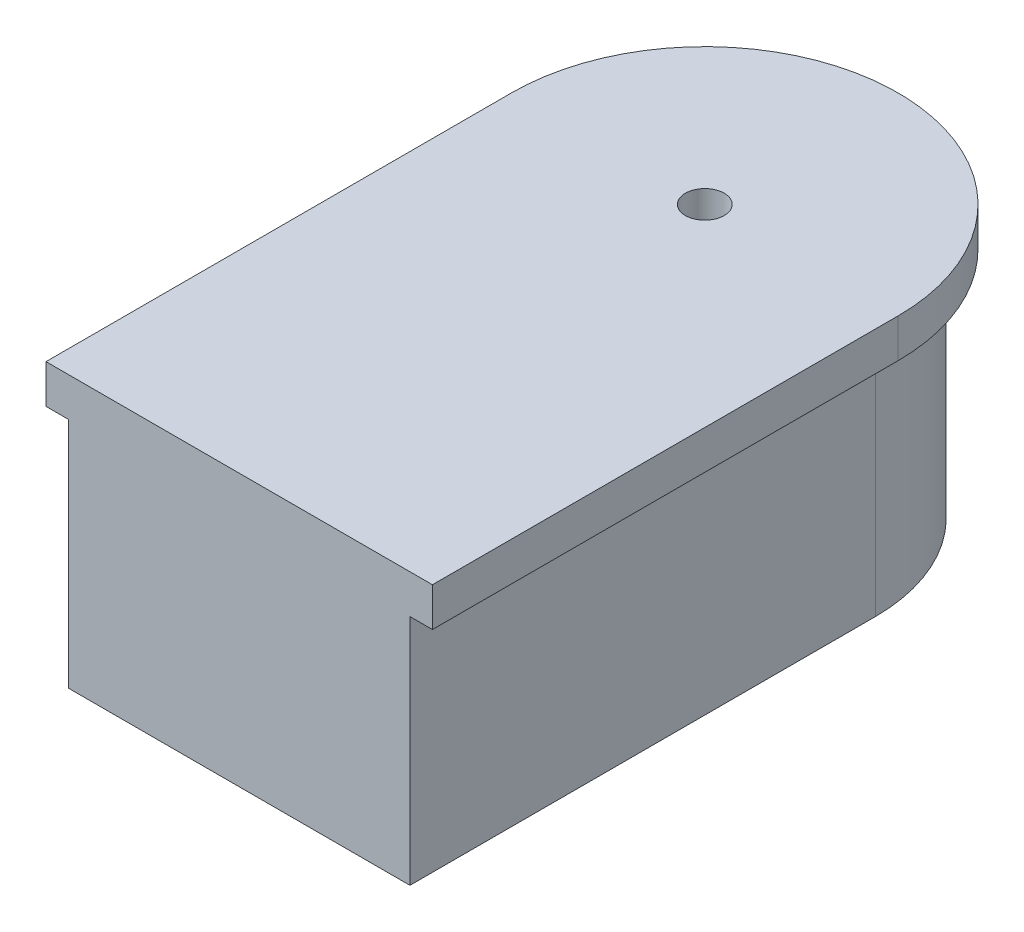
SolidWorks part; units mm, degrees
ref_plane "Front Plane" through (0, 0, 0) normal (0, 0, 1) x (1, 0, 0)
ref_plane "Top Plane" through (0, 0, 0) normal (0, 1, 0) x (1, 0, 0)
ref_plane "Right Plane" through (0, 0, 0) normal (1, 0, 0) x (0, 0, -1)
sketch "Sketch1" plane through (0, 0, 0) normal (0, 1, 0) x (1, 0, 0)
  line L1 (0, 0) -> (44, 0)
  line L2 (0, 0) -> (0, 60)
  line L4 (44, 0) -> (44, 60)
  arc A0 (0, 60) -> (44, 60) centre (22, 60) cw
  dimension "D1" = 60
  dimension "D2" = 44
extrude "Boss-Extrude1" add sketch "Sketch1" along normal blind 30
sketch "Sketch2" plane through (0, 30, 0) normal (0, 1, 0) x (1, 0, 0)
  line L0 (0, 0) -> (44, 0) construction
  line L1 (46.9, 0) -> (-2.9, 0)
  line L2 (46.9, 0) -> (46.9, 60)
  line L4 (-2.9, 0) -> (-2.9, 60)
  line L5 (44, 0) -> (44, 60) construction
  arc A0 (-2.9, 60) -> (46.9, 60) centre (22, 60) cw
  dimension "D1" = 60
  dimension "D2" = 49.8
  dimension "D3" = 2.9
extrude "Boss-Extrude2" add sketch "Sketch2" along normal blind 5
sketch "Sketch3" plane through (0, 35, 0) normal (0, 1, 0) x (1, 0, 0)
  circle A0 centre (22, 60) radius 2.5
  dimension "D1" = 5
extrude "Cut-Extrude1" cut sketch "Sketch3" against normal through all
